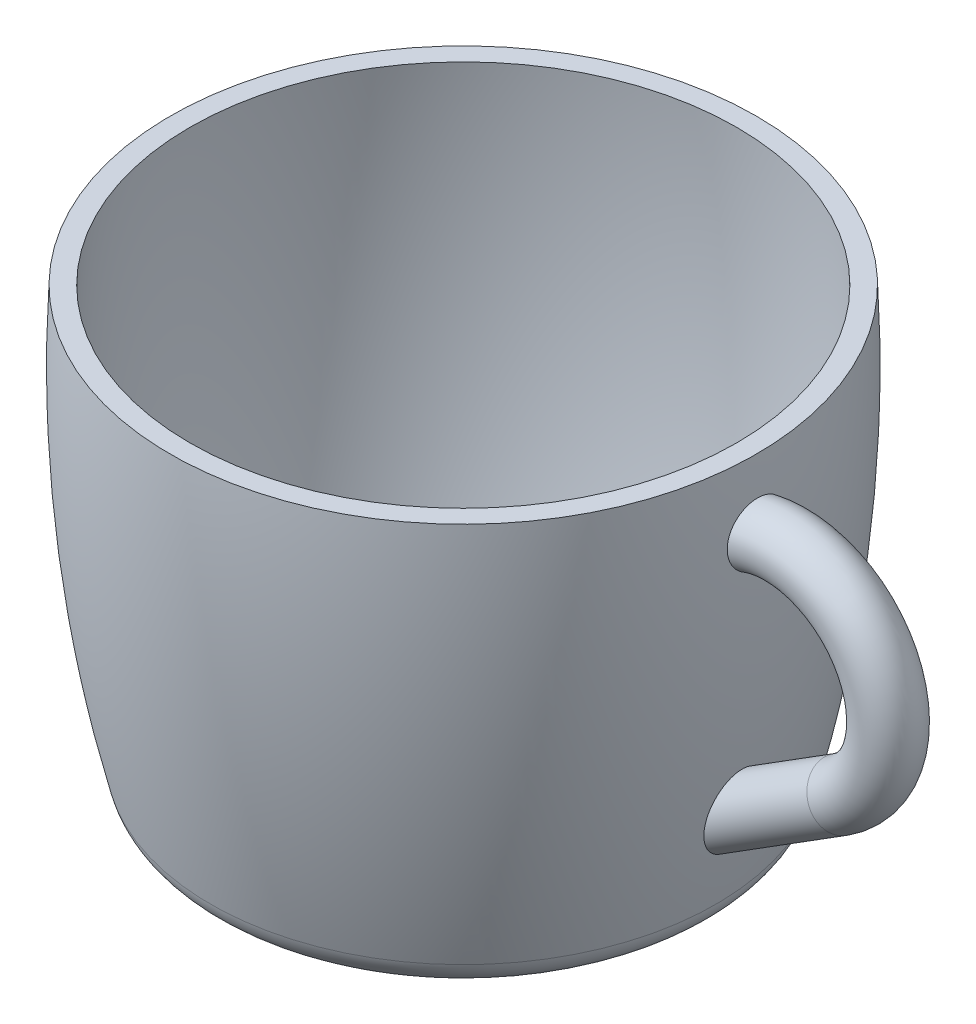
SolidWorks part; units mm, degrees
ref_plane "前视基准面" through (0, 0, 0) normal (0, 0, 1) x (1, 0, 0)
ref_plane "上视基准面" through (0, 0, 0) normal (0, 1, 0) x (1, 0, 0)
ref_plane "右视基准面" through (0, 0, 0) normal (1, 0, 0) x (0, 0, -1)
other "Configuration Table"
sketch "草图1" plane through (0, 0, 0) normal (0, 0, 1) x (1, 0, 0)
  line L0 (0, 0) -> (-22, 0)
  line L1 (-30, 45) -> (-27.9974, 45)
  line L2 (0, 0) -> (0, 45) construction
  line L3 (0, 2) -> (-23.5512, 2)
  line L4 (0, 2) -> (26.5102, 2) construction
  line L5 (0, 2) -> (0, 0)
  arc A0 (-22, 0) -> (-25.8797, 3.0265) centre (-22, 4) cw
  arc A1 (-25.8797, 3.0265) -> (-30, 45) centre (112.8202, 37.8308) cw
  arc A2 (-27.9974, 45) -> (-23.0489, 0.14) centre (112.8202, 37.8308) ccw
  point P2 (0, 0)
  dimension "D1" = 22
  dimension "D2" = 4
  dimension "D3" = 143
  dimension "D6" = 2
  dimension "D4" = 45
  dimension "D5" = 30
revolve "旋转4" add sketch "草图1" angle 360 about L2
ref_plane "基准面1" through (0, 0, 0) normal (0, 0, 1) x (1, 0, 0)
sketch "草图2" plane through (0, 0, 0) normal (0, 0, 1) x (1, 0, 0)
  line L0 (21.4591, 8.3515) -> (38.5849, 19.1085)
  line L1 (0, 0) -> (43.0344, 0)
  line L3 (0, 3.0265) -> (25.8797, 3.0265)
  line L4 (25.8797, 3.0265) -> (-25.8797, 3.0265) construction
  line L5 (0, 3.0265) -> (0, 45)
  line L6 (0, 45) -> (30, 45)
  line L7 (30, 45) -> (-30, 45) construction
  line L8 (38.5849, 19.1085) -> (33, 28)
  line L9 (33, 28) -> (27.4151, 36.8915)
  arc A0 (38.5849, 19.1085) -> (27.4151, 36.8915) centre (33, 28) ccw
  arc A3 (25.8797, 3.0265) -> (30, 45) centre (-112.8202, 37.8308) ccw construction
  dimension "D1" = 33
  dimension "D3" = 21
  dimension "D2" = 17
sweep "扫描3" add path "草图2" circular profile diameter 6 parameters "D3"=6
